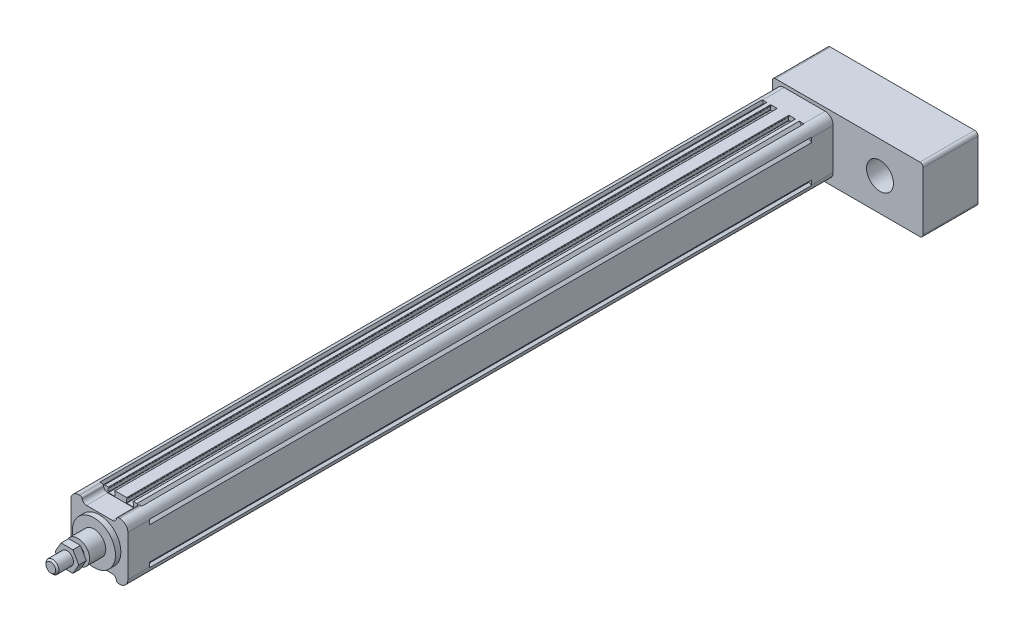
SolidWorks part; units mm, degrees
ref_plane "Front" through (0, 0, 0) normal (0, 0, 1) x (1, 0, 0)
ref_plane "Top" through (0, 0, 0) normal (0, 1, 0) x (1, 0, 0)
ref_plane "Right" through (0, 0, 0) normal (1, 0, 0) x (0, 0, -1)
sketch "草图1" plane through (0, 0, 0) normal (0, 0, 1) x (1, 0, 0)
  line L0 (19.7737, 3) -> (23.3, 3)
  line L1 (23.3, 3) -> (23.3, -3)
  line L2 (23.3, -3) -> (19.7737, -3)
  line L3 (-19.7737, -3) -> (-23.3, -3)
  line L4 (-23.3, -3) -> (-23.3, 3)
  line L5 (-23.3, 3) -> (-19.7737, 3)
  line L6 (-18.2, 24) -> (-19.4434, 26.4869)
  line L7 (-26.4869, 19.4434) -> (-24, 18.2)
  line L8 (-24, 18.2) -> (-24, 17.1)
  line L9 (-24, 17.1) -> (-26.5, 15)
  line L10 (-26.5, 15) -> (-26.5, -15)
  line L11 (-26.5, -15) -> (-24, -17.1)
  line L12 (-24, -17.1) -> (-24, -18.2)
  line L13 (-24, -18.2) -> (-26.4869, -19.4434)
  line L14 (-19.4434, -26.4869) -> (-18.2, -24)
  line L15 (-18.2, -24) -> (-17.1, -24)
  line L16 (-17.1, -24) -> (-15, -26.5)
  line L17 (-15, -26.5) -> (-11.65, -26.5)
  line L18 (-11.25, -26.1) -> (-11.25, -25.6)
  line L19 (-11.65, -25.2) -> (-11.75, -25.2)
  line L20 (-11.75, -25.2) -> (-11.75, -22.4)
  line L21 (-11.35, -22) -> (-5.65, -22)
  line L22 (-5.25, -22.4) -> (-5.25, -25.2)
  line L23 (-5.25, -25.2) -> (-5.35, -25.2)
  line L24 (-5.75, -25.6) -> (-5.75, -26.1)
  line L25 (-5.35, -26.5) -> (5.35, -26.5)
  line L26 (5.75, -26.1) -> (5.75, -25.6)
  line L27 (5.35, -25.2) -> (5.25, -25.2)
  line L28 (5.25, -25.2) -> (5.25, -22.4)
  line L29 (5.65, -22) -> (11.35, -22)
  line L30 (11.75, -22.4) -> (11.75, -25.2)
  line L31 (11.75, -25.2) -> (11.65, -25.2)
  line L32 (11.25, -25.6) -> (11.25, -26.1)
  line L33 (11.65, -26.5) -> (15, -26.5)
  line L34 (15, -26.5) -> (17.1, -24)
  line L35 (17.1, -24) -> (18.2, -24)
  line L36 (18.2, -24) -> (19.4434, -26.4869)
  line L37 (26.4869, -19.4434) -> (24, -18.2)
  line L38 (24, -18.2) -> (24, -17.1)
  line L39 (24, -17.1) -> (26.5, -15)
  line L40 (26.5, -15) -> (26.5, 15)
  line L41 (26.5, 15) -> (24, 17.1)
  line L42 (24, 17.1) -> (24, 18.2)
  line L43 (24, 18.2) -> (26.4869, 19.4434)
  line L44 (19.4434, 26.4869) -> (18.2, 24)
  line L45 (18.2, 24) -> (17.1, 24)
  line L46 (17.1, 24) -> (15, 26.5)
  line L47 (15, 26.5) -> (11.65, 26.5)
  line L48 (11.25, 26.1) -> (11.25, 25.6)
  line L49 (11.65, 25.2) -> (11.75, 25.2)
  line L50 (11.75, 25.2) -> (11.75, 22.4)
  line L51 (11.35, 22) -> (5.65, 22)
  line L52 (5.25, 22.4) -> (5.25, 25.2)
  line L53 (5.25, 25.2) -> (5.35, 25.2)
  line L54 (5.75, 25.6) -> (5.75, 26.1)
  line L55 (5.35, 26.5) -> (-5.35, 26.5)
  line L56 (-5.75, 26.1) -> (-5.75, 25.6)
  line L57 (-5.35, 25.2) -> (-5.25, 25.2)
  line L58 (-5.25, 25.2) -> (-5.25, 22.4)
  line L59 (-5.65, 22) -> (-11.35, 22)
  line L60 (-11.75, 22.4) -> (-11.75, 25.2)
  line L61 (-11.75, 25.2) -> (-11.65, 25.2)
  line L62 (-11.25, 25.6) -> (-11.25, 26.1)
  line L63 (-11.65, 26.5) -> (-15, 26.5)
  line L64 (-15, 26.5) -> (-17.1, 24)
  line L65 (-17.1, 24) -> (-18.2, 24)
  arc A0 (19.7737, 3) -> (-19.7737, 3) centre (0, 0) ccw
  arc A1 (-19.7737, -3) -> (19.7737, -3) centre (0, 0) ccw
  circle A2 centre (19, 19) radius 2.1
  circle A3 centre (19, -19) radius 2.1
  circle A4 centre (-19, -19) radius 2.1
  circle A5 centre (-19, 19) radius 2.1
  arc A6 (-19.4434, 26.4869) -> (-26.4869, 19.4434) centre (-19, 19) ccw
  arc A7 (-26.4869, -19.4434) -> (-19.4434, -26.4869) centre (-19, -19) ccw
  arc A8 (-11.65, -26.5) -> (-11.25, -26.1) centre (-11.65, -26.1) ccw
  arc A9 (-11.25, -25.6) -> (-11.65, -25.2) centre (-11.65, -25.6) ccw
  arc A10 (-11.35, -22) -> (-11.75, -22.4) centre (-11.35, -22.4) ccw
  arc A11 (-5.25, -22.4) -> (-5.65, -22) centre (-5.65, -22.4) ccw
  arc A12 (-5.35, -25.2) -> (-5.75, -25.6) centre (-5.35, -25.6) ccw
  arc A13 (-5.75, -26.1) -> (-5.35, -26.5) centre (-5.35, -26.1) ccw
  arc A14 (5.35, -26.5) -> (5.75, -26.1) centre (5.35, -26.1) ccw
  arc A15 (5.75, -25.6) -> (5.35, -25.2) centre (5.35, -25.6) ccw
  arc A16 (5.65, -22) -> (5.25, -22.4) centre (5.65, -22.4) ccw
  arc A17 (11.75, -22.4) -> (11.35, -22) centre (11.35, -22.4) ccw
  arc A18 (11.65, -25.2) -> (11.25, -25.6) centre (11.65, -25.6) ccw
  arc A19 (11.25, -26.1) -> (11.65, -26.5) centre (11.65, -26.1) ccw
  arc A20 (19.4434, -26.4869) -> (26.4869, -19.4434) centre (19, -19) ccw
  arc A21 (26.4869, 19.4434) -> (19.4434, 26.4869) centre (19, 19) ccw
  arc A22 (11.65, 26.5) -> (11.25, 26.1) centre (11.65, 26.1) ccw
  arc A23 (11.25, 25.6) -> (11.65, 25.2) centre (11.65, 25.6) ccw
  arc A24 (11.35, 22) -> (11.75, 22.4) centre (11.35, 22.4) ccw
  arc A25 (5.25, 22.4) -> (5.65, 22) centre (5.65, 22.4) ccw
  arc A26 (5.35, 25.2) -> (5.75, 25.6) centre (5.35, 25.6) ccw
  arc A27 (5.75, 26.1) -> (5.35, 26.5) centre (5.35, 26.1) ccw
  arc A28 (-5.35, 26.5) -> (-5.75, 26.1) centre (-5.35, 26.1) ccw
  arc A29 (-5.75, 25.6) -> (-5.35, 25.2) centre (-5.35, 25.6) ccw
  arc A30 (-5.65, 22) -> (-5.25, 22.4) centre (-5.65, 22.4) ccw
  arc A31 (-11.75, 22.4) -> (-11.35, 22) centre (-11.35, 22.4) ccw
  arc A32 (-11.65, 25.2) -> (-11.25, 25.6) centre (-11.65, 25.6) ccw
  arc A33 (-11.25, 26.1) -> (-11.65, 26.5) centre (-11.65, 26.1) ccw
extrude "凸台-拉伸1" add sketch "草图1" along normal blind 615
sketch "草图6" plane through (0, 0, 615) normal (0, 0, 1) x (1, 0, 0)
  line L0 (0, 0) -> (19, 0) construction
  line L2 (-26.5, -19) -> (-26.5, 19)
  line L3 (-19, 26.5) -> (-17.9161, 26.5)
  line L4 (26.5, -19) -> (26.5, 19)
  line L5 (-26.5, -26.5) -> (26.5, 26.5) construction
  line L6 (-26.5, 26.5) -> (26.5, -26.5) construction
  line L7 (-12, 21.5) -> (12, 21.5)
  line L9 (19, 26.5) -> (17.9161, 26.5)
  line L10 (19, -26.5) -> (17.9161, -26.5)
  line L11 (-12, -21.5) -> (12, -21.5)
  line L12 (-19, -26.5) -> (-17.9161, -26.5)
  arc A0 (12, 21.5) -> (15.9441, 24.8333) centre (12, 25.5) ccw
  arc A1 (-15.9441, 24.8333) -> (-12, 21.5) centre (-12, 25.5) ccw
  arc A2 (-15.9441, 24.8333) -> (-17.9161, 26.5) centre (-17.9161, 24.5) ccw
  arc A3 (15.9441, 24.8333) -> (17.9161, 26.5) centre (17.9161, 24.5) cw
  arc A4 (-26.5, -19) -> (-19, -26.5) centre (-19, -19) ccw
  arc A5 (19, -26.5) -> (26.5, -19) centre (19, -19) ccw
  arc A6 (26.5, 19) -> (19, 26.5) centre (19, 19) ccw
  arc A7 (-26.5, 19) -> (-19, 26.5) centre (-19, 19) cw
  arc A8 (15.9441, -24.8333) -> (17.9161, -26.5) centre (17.9161, -24.5) ccw
  arc A9 (12, -21.5) -> (15.9441, -24.8333) centre (12, -25.5) cw
  arc A10 (-15.9441, -24.8333) -> (-12, -21.5) centre (-12, -25.5) cw
  arc A11 (-15.9441, -24.8333) -> (-17.9161, -26.5) centre (-17.9161, -24.5) cw
  point P0 (0, 0)
  point P9 (0, 21.5)
  point P13 (20, 20.8461)
  point P16 (-12, 20.8461)
  dimension "D5" = 4
  dimension "D6" = 2
  dimension "D7" = 2
  dimension "D9" = 7.5
  dimension "D1" = 53
  dimension "D2" = 53
  dimension "D3" = 26.5
  dimension "D4" = 24
  dimension "D8" = 5
extrude "凸台-拉伸2" add sketch "草图6" along normal blind 20
sketch "草图7" plane through (0, 0, 635) normal (0, 0, 1) x (1, 0, 0)
  circle A0 centre (0, 0) radius 20
  dimension "D1" = 40
extrude "凸台-拉伸3" add sketch "草图7" along normal blind 5
sketch "草图9" plane through (0, 0, 640) normal (0, 0, 1) x (1, 0, 0)
  circle A0 centre (0, 0) radius 11
  dimension "D1" = 22
extrude "凸台-拉伸4" add sketch "草图9" along normal blind 15
sketch "草图10" plane through (0, 0, 655) normal (0, 0, 1) x (1, 0, 0)
  circle A0 centre (0, 0) radius 6
  dimension "D1" = 12
extrude "凸台-拉伸5" add sketch "草图10" along normal blind 25
sketch "草图11" plane through (0, 0, 0) normal (0, 0, -1) x (-1, 0, 0)
  line L1 (-19, -26.5) -> (19, -26.5)
  line L2 (-26.5, -19) -> (-26.5, 19)
  line L3 (-19, 26.5) -> (19, 26.5)
  line L4 (26.5, -19) -> (26.5, 19)
  line L5 (-26.5, -26.5) -> (26.5, 26.5) construction
  line L6 (-26.5, 26.5) -> (26.5, -26.5) construction
  arc A0 (-26.5, -19) -> (-19, -26.5) centre (-19, -19) ccw
  arc A1 (19, -26.5) -> (26.5, -19) centre (19, -19) ccw
  arc A2 (26.5, 19) -> (19, 26.5) centre (19, 19) ccw
  arc A3 (-26.5, 19) -> (-19, 26.5) centre (-19, 19) cw
  point P0 (0, 0)
  dimension "D3" = 7.5
  dimension "D1" = 53
  dimension "D2" = 53
extrude "凸台-拉伸6" add sketch "草图11" along normal blind 20
sketch "草图12" plane through (0, 0, -20) normal (0, 0, -1) x (-1, 0, 0)
  line L1 (-107, -30.4042) -> (27, -30.4042)
  line L2 (-110, -27.4042) -> (-110, 26.5958)
  line L3 (-107, 29.5958) -> (27, 29.5958)
  line L4 (30, -27.4042) -> (30, 26.5958)
  line L5 (-110, -30.4042) -> (30, 29.5958) construction
  line L6 (-110, 29.5958) -> (30, -30.4042) construction
  arc A0 (27, 29.5958) -> (30, 26.5958) centre (27, 26.5958) cw
  arc A1 (30, -27.4042) -> (27, -30.4042) centre (27, -27.4042) cw
  arc A2 (-110, -27.4042) -> (-107, -30.4042) centre (-107, -27.4042) ccw
  arc A3 (-110, 26.5958) -> (-107, 29.5958) centre (-107, 26.5958) cw
  point P0 (-40, -0.4042)
  dimension "D4" = 3
  dimension "D1" = 60
  dimension "D2" = 140
  dimension "D3" = 30
extrude "凸台-拉伸7" add sketch "草图12" along normal blind 51
sketch "草图13" plane through (0, 0, -20) normal (0, 0, 1) x (1, 0, 0)
  circle A0 centre (70, 0) radius 12.5
  dimension "D2" = 25
  dimension "D1" = 70
extrude "切除-拉伸2" cut sketch "草图13" against normal blind 30
hole_wizard "M6 螺纹孔1" positions "草图14" profile "草图15" tap size "M6" standard "GB"
sketch "草图14" plane through (0, 0, -71) normal (0, 0, -1) x (-1, 0, 0)
  line L0 (30, -27.4042) -> (30, 26.5958) construction
  point P0 (19, -19)
  dimension "D1" = 11
  dimension "D2" = 19
sketch "草图15" plane through (-19, -19, -71) normal (1, 0, 0) x (0, 1, 0)
  line L0 (0, 0) -> (0, 16.5022)
  line L1 (0, 16.5022) -> (2.5, 15)
  line L2 (2.5, 15) -> (2.5, 0)
  line L5 (2.5, 0) -> (0, 0)
  line L10 (0, 16.5022) -> (-2.5, 15) construction
  line L11 (0, -6.35) -> (0, 107.95) construction
  dimension "螺纹孔钻头直径" = 5
  dimension "螺纹孔钻头深度" = 15
  dimension "导头角度" = 118
cosmetic thread "孔螺蚊线4" parameters "D1"=12, "D2"=6
pattern_linear "阵列(线性)1" count 2 spacing 38 along (0, 1, 0) count 2 spacing 38 along (1, 0, 0) of "M6 螺纹孔1"
hole_wizard "M6 螺纹孔2" positions "草图16" profile "草图17" tap size "M6" standard "GB"
sketch "草图16" plane through (0, 0, -71) normal (0, 0, -1) x (-1, 0, 0)
  circle A1 centre (-19, 19) radius 2.5 construction
  circle A2 centre (-19, -19) radius 2.5 construction
  point P0 (-84, -19)
  point P2 (-84, 19)
  dimension "D3" = 65
  dimension "D1" = 19
  dimension "D2" = 19
  dimension "D4" = 65
sketch "草图17" plane through (84, -19, -71) normal (1, 0, 0) x (0, 1, 0)
  line L0 (0, 0) -> (0, 16.5022)
  line L1 (0, 16.5022) -> (2.5, 15)
  line L2 (2.5, 15) -> (2.5, 0)
  line L5 (2.5, 0) -> (0, 0)
  line L10 (0, 16.5022) -> (-2.5, 15) construction
  line L11 (0, -6.35) -> (0, 107.95) construction
  dimension "螺纹孔钻头直径" = 5
  dimension "螺纹孔钻头深度" = 15
  dimension "导头角度" = 118
cosmetic thread "孔螺蚊线5" parameters "D1"=12, "D2"=6
cosmetic thread "孔螺蚊线6" parameters "D1"=12, "D2"=6
hole_wizard "M6 螺纹孔3" positions "草图19" profile "草图20" tap size "M6" standard "GB"
sketch "草图19" plane through (-26.5, 0, 0) normal (-1, 0, 0) x (0, 0, 1)
  line L0 (635, 19) -> (635, -19) construction
  point P0 (625, 11)
  point P2 (625, -11)
  dimension "D1" = 10
  dimension "D2" = 10
  dimension "D3" = 22
  dimension "D4" = 11
sketch "草图20" plane through (-26.5, 11, 625) normal (0, 1, 0) x (0, 0, 1)
  line L0 (0, 0) -> (0, 16.5022)
  line L1 (0, 16.5022) -> (2.5, 15)
  line L2 (2.5, 15) -> (2.5, 0)
  line L5 (2.5, 0) -> (0, 0)
  line L10 (0, 16.5022) -> (-2.5, 15) construction
  line L11 (0, -6.35) -> (0, 107.95) construction
  dimension "螺纹孔钻头直径" = 5
  dimension "螺纹孔钻头深度" = 15
  dimension "导头角度" = 118
cosmetic thread "孔螺蚊线7" parameters "D1"=12, "D2"=6
cosmetic thread "孔螺蚊线8" parameters "D1"=12, "D2"=6
hole_wizard "M6 螺纹孔4" positions "草图21" profile "草图22" tap size "M6" standard "GB"
sketch "草图21" plane through (-26.5, 0, 0) normal (-1, 0, 0) x (0, 0, 1)
  line L0 (-20, -27.4042) -> (-20, 26.5958) construction
  line L1 (-20, -19) -> (-20, 19) construction
  point P0 (-10, 11)
  point P2 (-10, -11)
  dimension "D1" = 10
  dimension "D2" = 10
  dimension "D3" = 11
  dimension "D4" = 11
sketch "草图22" plane through (-26.5, 11, -10) normal (0, 1, 0) x (0, 0, 1)
  line L0 (0, 0) -> (0, 16.5022)
  line L1 (0, 16.5022) -> (2.5, 15)
  line L2 (2.5, 15) -> (2.5, 0)
  line L5 (2.5, 0) -> (0, 0)
  line L10 (0, 16.5022) -> (-2.5, 15) construction
  line L11 (0, -6.35) -> (0, 107.95) construction
  dimension "螺纹孔钻头直径" = 5
  dimension "螺纹孔钻头深度" = 15
  dimension "导头角度" = 118
cosmetic thread "孔螺蚊线9" parameters "D1"=12, "D2"=6
cosmetic thread "孔螺蚊线10" parameters "D1"=12, "D2"=6
chamfer "倒角1" distance 1.5 angle 45 1 edges at (6, 0, 680)
sketch "草图23" plane through (0, 0, 655) normal (0, 0, 1) x (1, 0, 0)
  line L1 (10.9697, 0) -> (5.4848, 9.5)
  line L2 (5.4848, 9.5) -> (-5.4848, 9.5)
  line L3 (-5.4848, 9.5) -> (-10.9697, 0)
  line L4 (-10.9697, 0) -> (-5.4848, -9.5)
  line L5 (-5.4848, -9.5) -> (5.4848, -9.5)
  line L6 (5.4848, -9.5) -> (10.9697, 0)
  circle A0 centre (0, 0) radius 9.5 construction
  dimension "D1" = 19
extrude "凸台-拉伸8" add sketch "草图23" along normal blind 7 from offset 3
